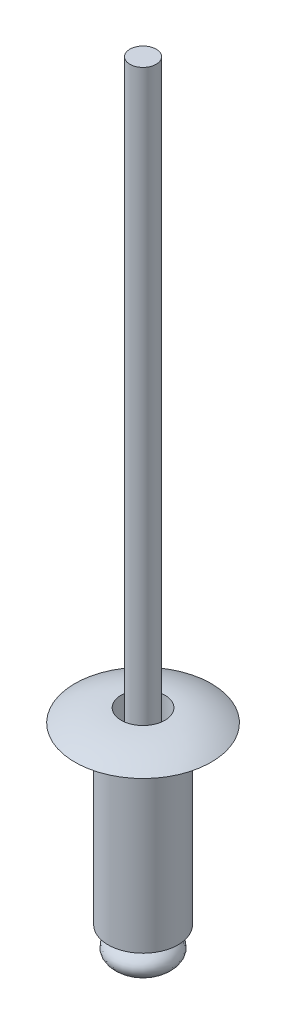
SolidWorks part; units mm, degrees
material "AISI 316 Arkusz stali nierdzewnej (SS)"
ref_plane "Płaszczyzna przednia" through (0, 0, 0) normal (0, 0, 1) x (1, 0, 0)
ref_plane "Płaszczyzna górna" through (0, 0, 0) normal (0, 1, 0) x (1, 0, 0)
ref_plane "Płaszczyzna prawa" through (0, 0, 0) normal (1, 0, 0) x (0, 0, -1)
sketch "Szkic1" plane through (0, 0, 0) normal (0, 0, 1) x (1, 0, 0)
  line L0 (0, 0) -> (0, 43) construction
  line L1 (-1.25, 10.75) -> (-1.25, 0)
  line L2 (-1.25, 0) -> (-2, 0)
  line L3 (-2, 0) -> (-2, 10)
  line L4 (-2, 10) -> (-3.9, 10)
  line L5 (-1.24, 1) -> (-1.24, -0.5)
  line L6 (0, 0) -> (0, -2) construction
  line L8 (-1.24, 1) -> (-0.75, 1)
  line L9 (-0.75, 1) -> (-0.75, 43)
  line L10 (-0.75, 43) -> (0, 43)
  line L11 (0, 43) -> (0, -2)
  arc A0 (-1.25, 10.75) -> (-3.9, 10) centre (-1.25, 5.6933) ccw
  ellipse E0 centre (0, -1.1206) end of major axis (-1.75, -1.1206) minor radius 0.8794 (-1.24, -0.5) -> (0, -2) ccw
  dimension "D5" = 10
  dimension "D1" = 4
  dimension "D2" = 2.5
  dimension "D3" = 7.8
  dimension "D4" = 0.75
  dimension "D6" = 0.5
  dimension "D7" = 1
  dimension "D8" = 2
  dimension "D9" = 3.5
  dimension "D10" = 45
  dimension "D11" = 1.5
  dimension "D12" = 0.01
revolve "Obrót1" add sketch "Szkic1" angle 360 about L0
